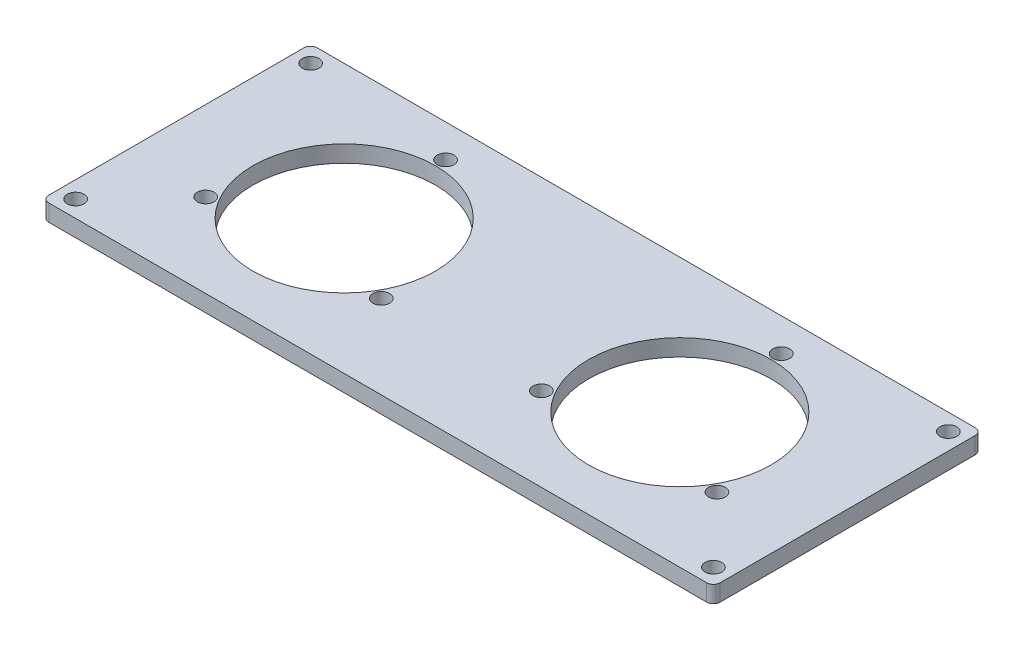
SolidWorks part; units mm, degrees
ref_plane "Front Plane" through (0, 0, 0) normal (0, 0, 1) x (1, 0, 0)
ref_plane "Top Plane" through (0, 0, 0) normal (0, 1, 0) x (1, 0, 0)
ref_plane "Right Plane" through (0, 0, 0) normal (1, 0, 0) x (0, 0, -1)
sketch "Sketch1" plane through (0, 0, 0) normal (0, 1, 0) x (1, 0, 0)
  line L0 (0, 50.8) -> (127, 50.8) construction
  line L1 (0, 0) -> (127, 0)
  line L2 (0, 0) -> (0, 101.6)
  line L3 (0, 101.6) -> (127, 101.6)
  line L4 (127, 0) -> (127, 101.6)
  line L5 (63.5, 50.8) -> (63.5, 89.154) construction
  circle A0 centre (63.5, 50.8) radius 34.544
  circle A2 centre (63.5, 50.8) radius 43.942 construction
  circle A4 centre (6.35, 95.25) radius 3.175
  circle A7 centre (6.35, 6.35) radius 3.175
  circle A8 centre (63.5, 89.154) radius 3.175
  circle A9 centre (96.7155, 31.623) radius 3.175
  circle A10 centre (30.2845, 31.623) radius 3.175
  point P12 (63.5, 85.344)
  point P13 (63.5, 50.8)
  point P24 (63.5, 50.8)
  dimension "D3" = 69.088
  dimension "D4" = 6.35
  dimension "D5" = 87.884
  dimension "D6" = 3.81
  dimension "D9" = 6.35
  dimension "D18" = 6.35
  dimension "D1" = 127
  dimension "D2" = 101.6
  dimension "D7" = 63.5
  dimension "D8" = 3
  dimension "D10" = 6.35
  dimension "D11" = 6.35
  dimension "D19" = 6.35
  dimension "D20" = 6.35
extrude "Boss-Extrude1" add sketch "Sketch1" along normal blind 6.35
fillet "Fillet1" radius 2.54 2 edges at (0, 3.175, -101.6) (0, 3.175, 0)
mirror "Mirror1" about plane through (127, 6.35, 0) normal (-1, 0, 0) of "Fillet1", "Boss-Extrude1"
